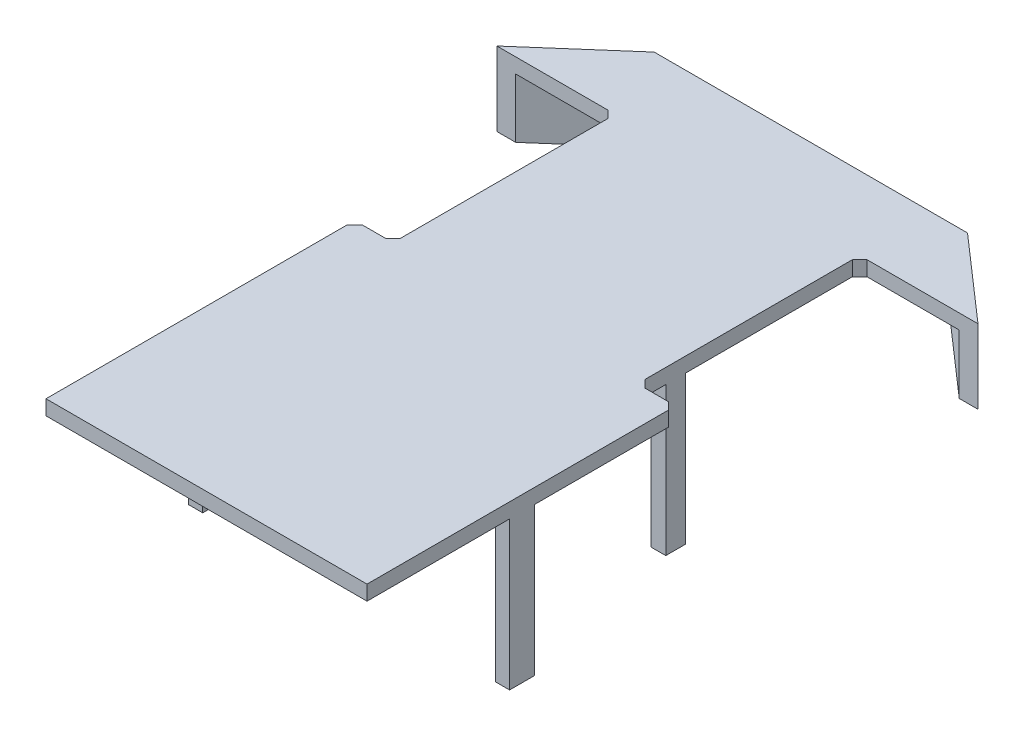
SolidWorks part; units mm, degrees
ref_plane "Front Plane" through (0, 0, 0) normal (0, 0, 1) x (1, 0, 0)
ref_plane "Top Plane" through (0, 0, 0) normal (0, 1, 0) x (1, 0, 0)
ref_plane "Right Plane" through (0, 0, 0) normal (1, 0, 0) x (0, 0, -1)
sketch "Sketch1" plane through (0, 0, 0) normal (0, 1, 0) x (1, 0, 0)
  line L0 (-49.5, -100.25) -> (-43.5, -100.25)
  line L1 (-49.5, -100.25) -> (-49.5, -108.25)
  line L2 (-49.5, -108.25) -> (-43.5, -108.25)
  line L3 (-43.5, -100.25) -> (-43.5, -108.25)
  line L4 (-65, -177) -> (-59.25, -177)
  line L5 (-65, -177) -> (-65, -187)
  line L6 (-65, -187) -> (-59.25, -187)
  line L7 (-59.25, -177) -> (-59.25, -187)
  line L8 (0, 145.8685) -> (0, -49854.1315) construction
  line L9 (65, -187) -> (59.25, -187)
  line L10 (59.25, -177) -> (59.25, -187)
  line L11 (65, -177) -> (59.25, -177)
  line L12 (65, -177) -> (65, -187)
  line L13 (49.5, -108.25) -> (43.5, -108.25)
  line L14 (43.5, -100.25) -> (43.5, -108.25)
  line L15 (49.5, -100.25) -> (43.5, -100.25)
  line L16 (49.5, -100.25) -> (49.5, -108.25)
  dimension "D1" = 8
  dimension "D2" = 6
  dimension "D3" = 10
  dimension "D4" = 5.75
  dimension "D5" = 59.25
  dimension "D6" = 43.5
  dimension "D7" = 68.75
  dimension "D8" = 100.25
extrude "Boss-Extrude1" add sketch "Sketch1" along normal blind 60
sketch "Sketch2" plane through (0, 60, 0) normal (0, 1, 0) x (1, 0, 0)
  line L0 (-52.5, -119.7204) -> (-62, -119.7204)
  line L1 (-62, -119.7204) -> (-65, -122.7204)
  line L2 (-65, -122.7204) -> (-65, -244.7204)
  line L3 (-65, -244.7204) -> (65, -244.7204)
  line L4 (65, -244.7204) -> (65, -122.7204)
  line L5 (65, -122.7204) -> (62, -119.7204)
  line L6 (62, -119.7204) -> (52.5, -119.7204)
  line L7 (52.5, -119.7204) -> (49.5, -116.7204)
  line L8 (49.5, -116.7204) -> (49.5, -32.7204)
  line L9 (49.5, -32.7204) -> (52.5, -29.7204)
  line L10 (52.5, -29.7204) -> (97.407, -29.7204)
  line L11 (97.407, -29.7204) -> (63.4409, 0)
  line L12 (63.4409, 0) -> (-63.4409, 0)
  line L13 (-63.4409, 0) -> (-97.407, -29.7204)
  line L14 (-97.407, -29.7204) -> (-52.5, -29.7204)
  line L15 (-52.5, -29.7204) -> (-49.5, -32.7204)
  line L16 (-49.5, -32.7204) -> (-49.5, -116.7204)
  line L17 (-49.5, -116.7204) -> (-52.5, -119.7204)
  point P19 (0, 0)
extrude "Boss-Extrude2" add sketch "Sketch2" along normal blind 6
sketch "Sketch4" plane through (0, 60, 0) normal (0, -1, 0) x (1, 0, 0)
  line L3 (97.407, 29.7204) -> (63.4409, 0) construction
  line L4 (63.4409, 0) -> (-63.4409, 0) construction
  line L5 (-63.4409, 0) -> (-97.407, 29.7204) construction
  line L6 (94.1145, 33.4833) -> (61.5622, 5)
  line L7 (61.5622, 5) -> (-61.5622, 5)
  line L8 (-61.5622, 5) -> (-94.1145, 33.4833)
  line L9 (89.8141, 29.7204) -> (61.5622, 5)
  line L10 (61.5622, 5) -> (-61.5622, 5)
  line L11 (-61.5622, 5) -> (-89.8141, 29.7204)
  line L12 (97.407, 29.7204) -> (63.4409, 0)
  line L13 (63.4409, 0) -> (-63.4409, 0)
  line L14 (-63.4409, 0) -> (-97.407, 29.7204)
  line L15 (-97.407, 29.7204) -> (-89.8141, 29.7204)
  line L16 (-97.407, 29.7204) -> (-52.5, 29.7204) construction
  line L17 (97.407, 29.7204) -> (89.8141, 29.7204)
  line L18 (52.5, 29.7204) -> (97.407, 29.7204) construction
  point P0 (-89.6845, 29.607)
  point P15 (97.407, 29.7204)
  dimension "D1" = 5
extrude "Boss-Extrude3" add sketch "Sketch4" along normal blind 24 contours L11 L15 L14 L13 L12 L17 L9 L10
